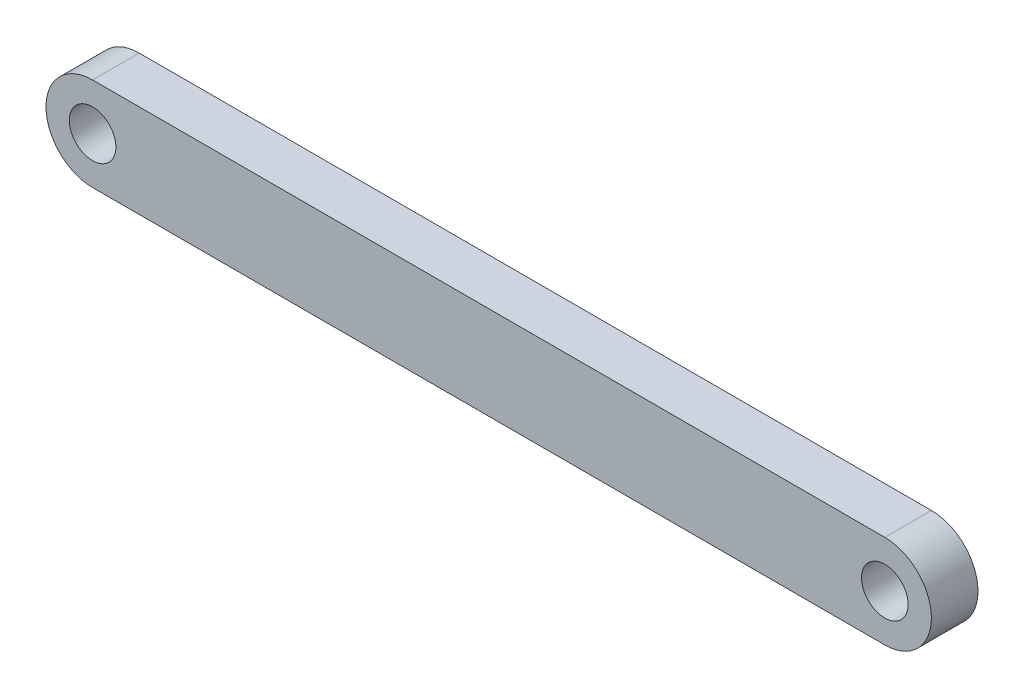
SolidWorks part; units mm, degrees
ref_plane "前基準面" through (0, 0, 0) normal (0, 0, 1) x (1, 0, 0)
ref_plane "上基準面" through (0, 0, 0) normal (0, 1, 0) x (1, 0, 0)
ref_plane "右基準面" through (0, 0, 0) normal (1, 0, 0) x (0, 0, -1)
sketch "草圖1" plane through (0, 0, 0) normal (0, 0, 1) x (1, 0, 0)
  line L0 (-17, 2.0009) -> (17, 2.0009)
  line L1 (-17, -1.9991) -> (17, -1.9991)
  arc A0 (-17, 2.0009) -> (-17, -1.9991) centre (-17, 0.0009) ccw
  arc A1 (17, -1.9991) -> (17, 2.0009) centre (17, 0.0009) ccw
  circle A2 centre (-17, 0.0009) radius 1
  circle A3 centre (17, 0.0009) radius 1
  dimension "D1" = 34
  dimension "D2" = 2
  dimension "D3" = 2
  dimension "D4" = 2
  dimension "D5" = 17
extrude "填料-伸長1" add sketch "草圖1" along normal blind 2
